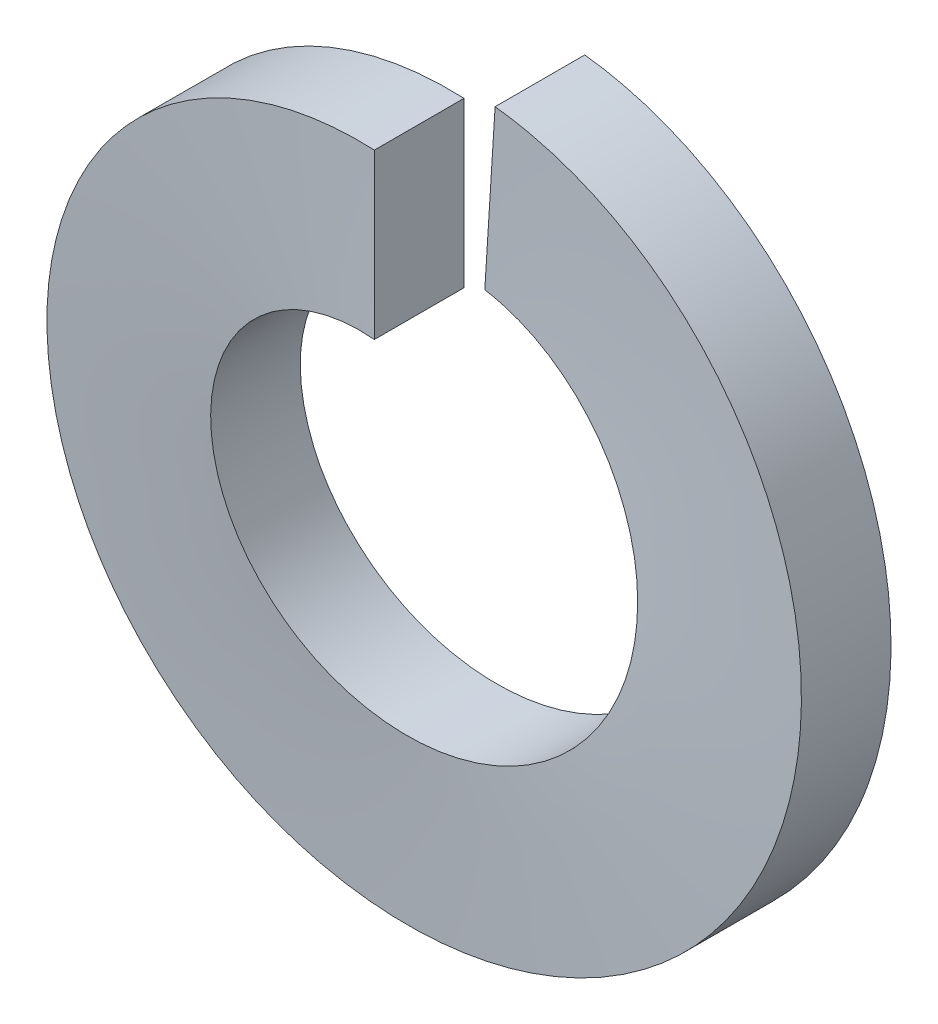
SolidWorks part; units mm, degrees
ref_plane "Front Plane" through (0, 0, 0) normal (0, 0, 1) x (1, 0, 0)
ref_plane "Top Plane" through (0, 0, 0) normal (0, 1, 0) x (1, 0, 0)
ref_plane "Right Plane" through (0, 0, 0) normal (1, 0, 0) x (0, 0, -1)
sketch "Sketch1" plane through (0, 0, 0) normal (0, 0, 1) x (1, 0, 0)
  line L0 (0, 6.1849) -> (0, 3.302) construction
  circle A0 centre (0, 0) radius 6.1849
  circle A1 centre (0, 0) radius 3.302 construction
  dimension "ID" = 6.604
  dimension "OD" = 12.3698
curve "Helix/Spiral1" pitch 1.7498 height 1.7323 turns 0.99 parameters "HT"=1.7323
sketch "Sketch2" plane through (0, 0, 0) normal (1, 0, 0) x (0, 0, -1)
  line L1 (0, 6.1849) -> (-1.5748, 6.1849)
  line L2 (0, 6.1849) -> (0, 3.302)
  line L3 (0, 3.302) -> (-1.5748, 3.302)
  line L4 (-1.5748, 6.1849) -> (-1.5748, 3.302)
  dimension "THK" = 1.5748
sweep "Sweep1" add profiles "Sketch2" path "Helix/Spiral1"
equation "\"HT@Helix/Spiral1\" = \"THK@Sketch2\"*1.1"
